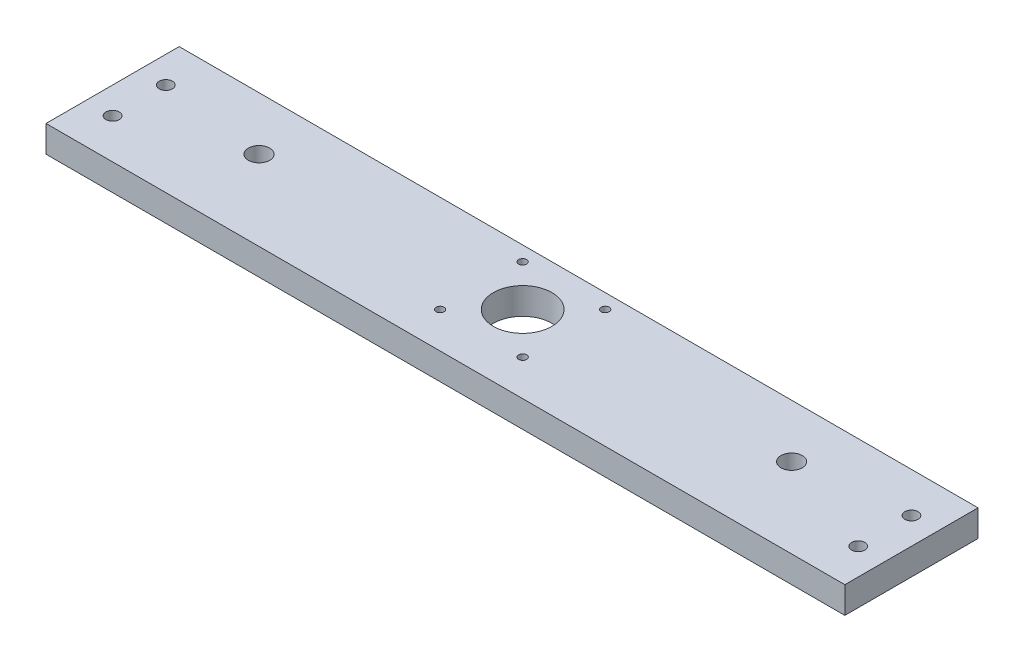
SolidWorks part; units mm, degrees
ref_plane "Front Plane" through (0, 0, 0) normal (0, 0, 1) x (1, 0, 0)
ref_plane "Top Plane" through (0, 0, 0) normal (0, 1, 0) x (1, 0, 0)
ref_plane "Right Plane" through (0, 0, 0) normal (1, 0, 0) x (0, 0, -1)
sketch "Sketch1" plane through (0, 0, 0) normal (0, 1, 0) x (1, 0, 0)
  line L0 (0, 20) -> (0, 0) construction
  line L1 (150, -30) -> (-150, -30)
  line L2 (150, -30) -> (150, 20)
  line L3 (150, 20) -> (-150, 20)
  line L4 (-150, -30) -> (-150, 20)
  line L5 (150, -30) -> (-150, 20) construction
  line L6 (150, 20) -> (-150, -30) construction
  line L7 (0, 0) -> (-100, 0) construction
  circle A0 centre (-100, 0) radius 4
  circle A1 centre (100, 0) radius 4
  point P0 (0, -5)
  dimension "D3" = 8
  dimension "D1" = 50
  dimension "D2" = 300
  dimension "D4" = 200
  dimension "D5" = 5
extrude "main" add sketch "Sketch1" along normal blind 10
sketch "Sketch4" plane through (0, 10, 0) normal (0, 1, 0) x (1, 0, 0)
  line L0 (0, 20) -> (0, -5) construction
  line L1 (150, 20) -> (-150, 20) construction
  line L2 (0, -5) -> (-150, -5) construction
  line L3 (-150, 20) -> (-150, -30) construction
  circle A0 centre (-140, 5) radius 2.5
  circle A1 centre (-140, -15) radius 2.5
  circle A2 centre (140, -15) radius 2.5
  circle A3 centre (140, 5) radius 2.5
  dimension "D1" = 5
  dimension "D2" = 10
  dimension "D3" = 20
extrude "mount" cut sketch "Sketch4" against normal through all
sketch "Sketch3" [suppressed] plane through (0, 10, 0) normal (0, 1, 0) x (1, 0, 0)
  line L0 (0, 20) -> (0, -1) construction
  line L1 (150, 20) -> (-150, 20) construction
  line L2 (0, -1) -> (-22.9552, -1) construction
  circle A0 centre (0, -1) radius 8.5
  point P2 (-100, 0)
  dimension "D1" = 17
  dimension "D2" = 1
sketch "Sketch2" plane through (0, 10, 0) normal (0, 1, 0) x (1, 0, 0)
  line L0 (0, -30) -> (0, -1) construction
  line L2 (-150, -30) -> (150, -30) construction
  line L4 (0, -1) -> (-150, -1) construction
  line L5 (-150, 20) -> (-150, -30) construction
  circle A6 centre (0, -1) radius 11
  circle A7 centre (15.5, -16.5) radius 1.5
  circle A8 centre (-15.5, -16.5) radius 1.5
  circle A9 centre (-15.5, 14.5) radius 1.5
  circle A10 centre (15.5, 14.5) radius 1.5
  point P17 (-100, 0)
  dimension "D1" = 1
  dimension "D4" = 31
  dimension "D2" = 22
  dimension "D3" = 3
  dimension "D5" = 31
extrude "stepper_mount" cut sketch "Sketch2" against normal through all
extrude "Cut-Extrude2" [suppressed] cut sketch "Sketch3" against normal through all
